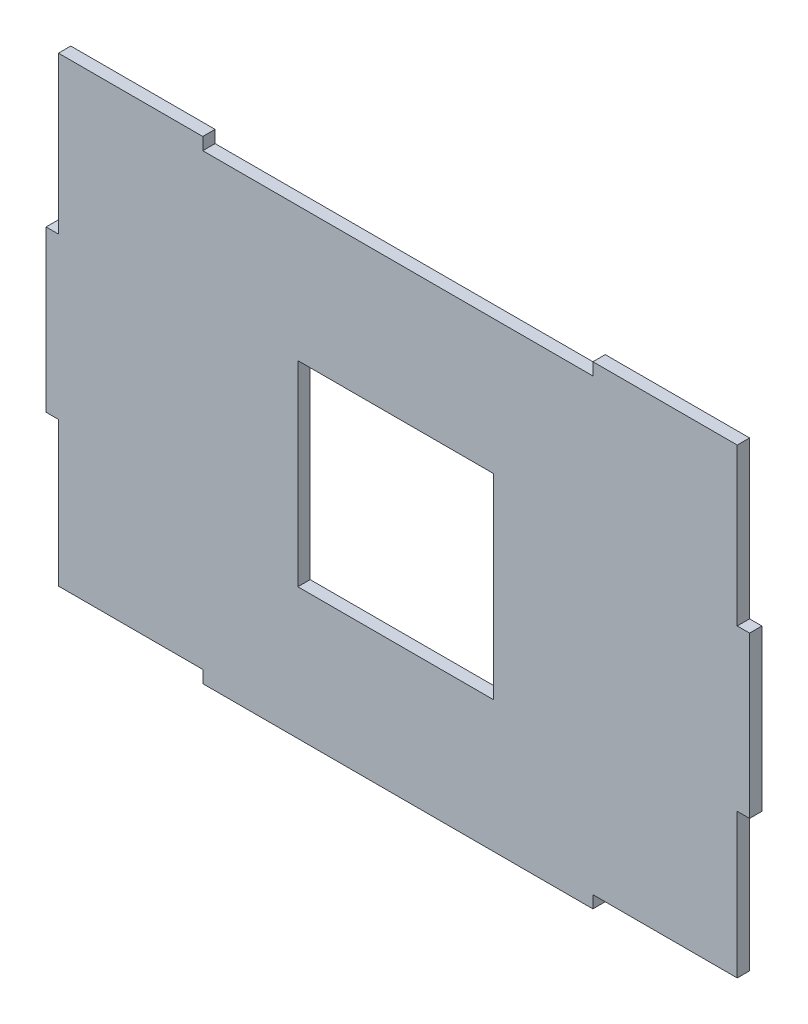
SolidWorks part; units mm, degrees
ref_plane "Front Plane" through (0, 0, 0) normal (0, 0, 1) x (1, 0, 0)
ref_plane "Top Plane" through (0, 0, 0) normal (0, 1, 0) x (1, 0, 0)
ref_plane "Right Plane" through (0, 0, 0) normal (1, 0, 0) x (0, 0, -1)
sketch "Sketch1" plane through (0, 0, 0) normal (0, 0, 1) x (1, 0, 0)
  line L1 (-31.623, -39.3567) -> (31.623, -39.3567)
  line L2 (-57.023, -13.9567) -> (-57.023, 12.065)
  line L4 (57.023, -13.9567) -> (57.023, 12.065)
  line L5 (-55.023, 12.065) -> (-55.023, 35.465)
  line L6 (-55.023, -37.3567) -> (-55.023, 35.465) construction
  line L7 (55.023, -37.3567) -> (55.023, -13.9567)
  line L8 (-55.023, -37.3567) -> (-31.623, -37.3567)
  line L9 (-55.023, -37.3567) -> (-55.023, -13.9567)
  line L10 (-31.623, 37.465) -> (-31.623, 35.465)
  line L11 (31.623, 37.465) -> (31.623, 35.465)
  line L12 (-57.023, 12.065) -> (-55.023, 12.065)
  line L13 (-57.023, -13.9567) -> (-55.023, -13.9567)
  line L14 (-57.023, 37.465) -> (57.023, 37.465) construction
  line L15 (-57.023, -39.3567) -> (-57.023, 37.465) construction
  line L16 (-57.023, -39.3567) -> (57.023, -39.3567) construction
  line L17 (57.023, -39.3567) -> (57.023, 37.465) construction
  line L19 (-55.023, 35.465) -> (55.023, 35.465) construction
  line L20 (55.023, 12.065) -> (55.023, 35.465)
  line L21 (31.623, -37.3567) -> (31.623, -39.3567)
  line L22 (55.023, 12.065) -> (57.023, 12.065)
  line L23 (55.023, -13.9567) -> (57.023, -13.9567)
  line L24 (55.023, -37.3567) -> (55.023, 35.465) construction
  line L25 (31.623, -37.3567) -> (55.023, -37.3567)
  line L26 (-31.623, -37.3567) -> (-31.623, -39.3567)
  line L27 (-55.023, -37.3567) -> (55.023, -37.3567) construction
  line L28 (31.623, 37.465) -> (55.023, 37.465)
  line L29 (-31.623, 35.465) -> (31.623, 35.465)
  line L30 (-55.023, 35.465) -> (-55.023, 37.465)
  line L31 (-55.023, 37.465) -> (-31.623, 37.465)
  line L32 (55.023, 35.465) -> (55.023, 37.465)
  line L39 (-16.2089, -18.0441) -> (15.5411, -18.0441)
  line L40 (-16.2089, -18.0441) -> (-16.2089, 13.7059)
  line L41 (-16.2089, 13.7059) -> (15.5411, 13.7059)
  line L42 (15.5411, -18.0441) -> (15.5411, 13.7059)
  line L57 (0, 35.465) -> (0, -39.3567) construction
  line L58 (-57.023, -0.9459) -> (57.023, -0.9459) construction
  dimension "D1" = 31.75
  dimension "D2" = 31.75
  dimension "D4" = 76.8217
  dimension "D5" = 25.4
  dimension "D6" = 25.4
  dimension "D7" = 25.4
  dimension "D9" = 114.046
  dimension "D3" = 2
extrude "Boss-Extrude1" add sketch "Sketch1" along normal blind 2
